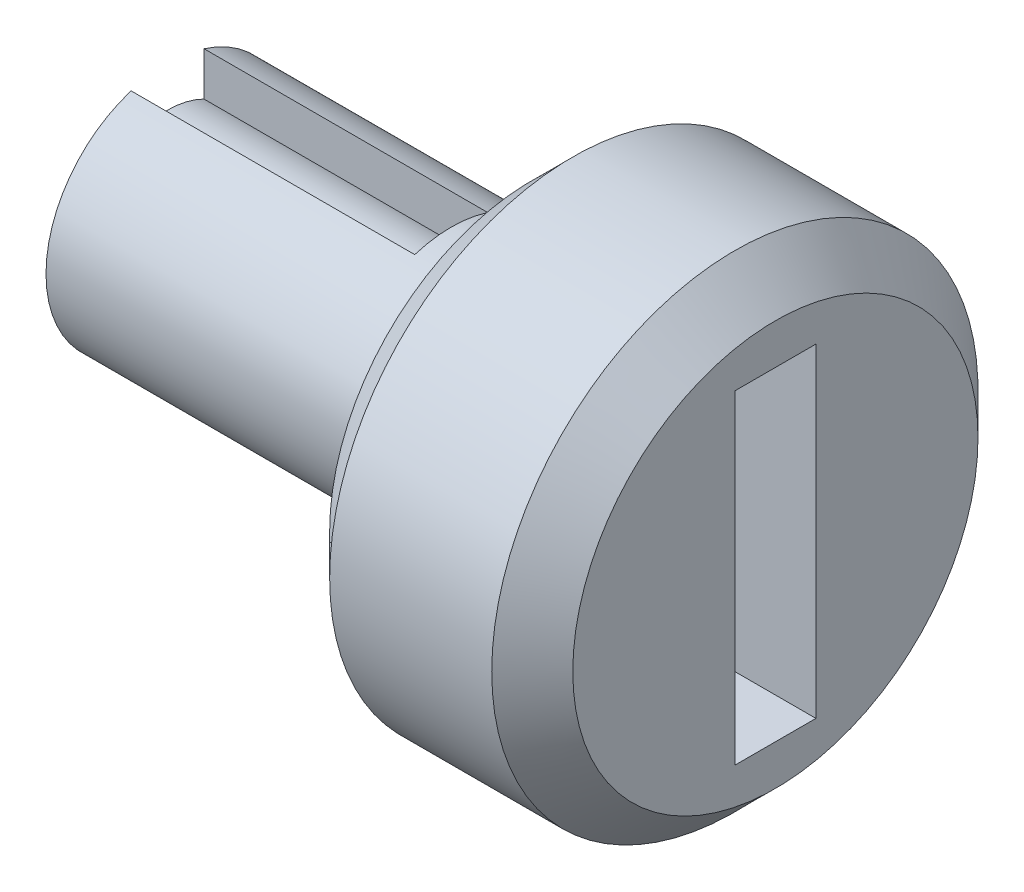
SolidWorks part; units mm, degrees
ref_plane "Front Plane" through (0, 0, 0) normal (0, 0, 1) x (1, 0, 0)
ref_plane "Top Plane" through (0, 0, 0) normal (0, 1, 0) x (1, 0, 0)
ref_plane "Right Plane" through (0, 0, 0) normal (1, 0, 0) x (0, 0, -1)
sketch "Sketch2" plane through (0, 0, 0) normal (0, 1, 0) x (1, 0, 0)
  line L0 (0, 0) -> (0, 3)
  line L1 (0, 3) -> (9, 3)
  line L2 (9, 3) -> (9, 6)
  line L3 (9, 6) -> (15, 6)
  line L4 (15, 6) -> (15, 0)
  line L5 (15, 0) -> (0, 0)
  line L6 (0, 0) -> (33.3109, 0) construction
  dimension "D1" = 15
  dimension "D2" = 6
  dimension "D3" = 6
  dimension "D4" = 12
revolve "Revolve1" add sketch "Sketch2" angle 360 about L6
sketch "Sketch3" plane through (0, 0, 0) normal (-1, 0, 0) x (0, 0, 1)
  circle A0 centre (0, 0) radius 1.2
  dimension "D1" = 2.4
extrude "Cut-Extrude1" cut sketch "Sketch3" against normal up to surface (9 mm away) up to face at (9, 0, 3)
cosmetic thread "Cosmetic Thread1" parameters "D2"=3
sketch "Sketch4" plane through (15, 0, 0) normal (1, 0, 0) x (0, 0, -1)
  line L1 (-1, -4) -> (1, -4)
  line L2 (-1, -4) -> (-1, 4)
  line L3 (-1, 4) -> (1, 4)
  line L4 (1, -4) -> (1, 4)
  line L5 (-1, -4) -> (1, 4) construction
  line L6 (-1, 4) -> (1, -4) construction
  point P0 (0, 0)
  dimension "D1" = 2
  dimension "D2" = 8
extrude "Cut-Extrude2" cut sketch "Sketch4" against normal blind 4
chamfer "Chamfer1" distance 1 angle 45 2 edges at (15, 0, 6) (9, 0, 6)
sketch "Sketch5" plane through (0, 0, 0) normal (-1, 0, 0) x (0, 0, 1)
  line L0 (-0.9, 2.3239) -> (0.9, 2.3239) construction
  line L1 (0, 2.3239) -> (0, 0) construction
  line L2 (-0.9, 2.8618) -> (-0.9, 1.7861)
  line L3 (0, 0) -> (0, -2.3239) construction
  line L4 (0.9, 2.8618) -> (0.9, 1.7861)
  line L5 (-0.9, -2.3239) -> (0.9, -2.3239) construction
  line L6 (-0.9, -1.7861) -> (-0.9, -2.8618)
  line L8 (0.9, -1.7861) -> (0.9, -2.8618)
  circle A0 centre (0, 0) radius 3 construction
  arc A1 (0.9, 2.8618) -> (-0.9, 2.8618) centre (0, 0) ccw
  arc A4 (-0.9, -2.8618) -> (0.9, -2.8618) centre (0, 0) ccw
  arc A6 (0.9, 1.7861) -> (-0.9, 1.7861) centre (0, 0) ccw
  arc A7 (-0.9, -1.7861) -> (0.9, -1.7861) centre (0, 0) ccw
  point P11 (0, -2.3239)
  dimension "D2" = 4
  dimension "D1" = 1.8
extrude "Cut-Extrude3" cut sketch "Sketch5" against normal offset from surface (7 mm away) 2 up to face at (9, 0, -5)
